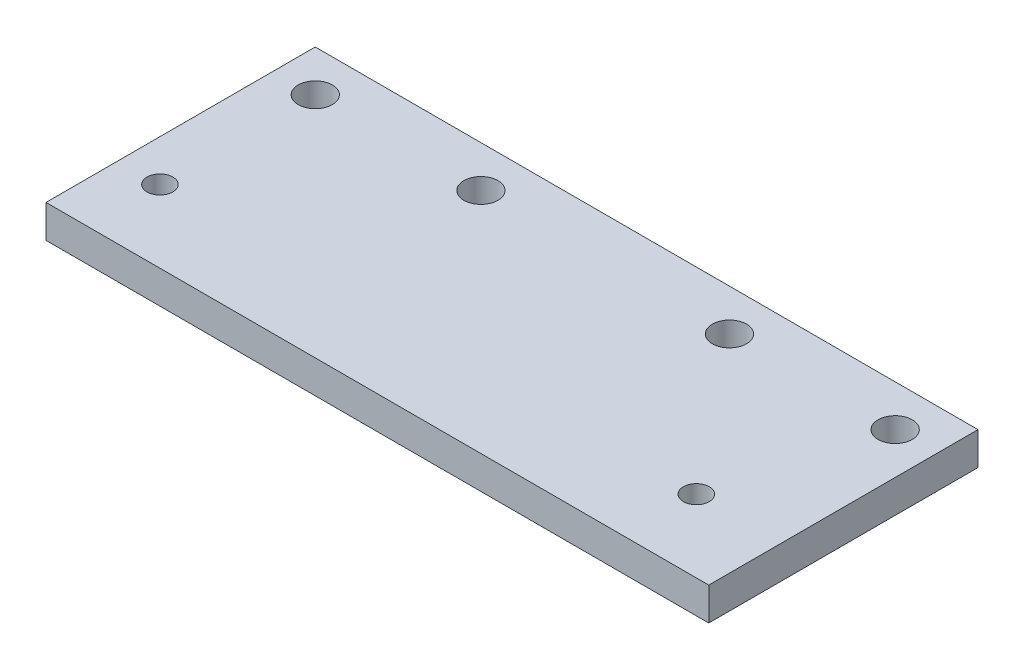
SolidWorks part; units mm, degrees
ref_plane "Front" through (0, 0, 0) normal (0, 0, 1) x (1, 0, 0)
ref_plane "Top" through (0, 0, 0) normal (0, 1, 0) x (1, 0, 0)
ref_plane "Right" through (0, 0, 0) normal (1, 0, 0) x (0, 0, -1)
sketch "Sketch1" plane through (0, 0, 0) normal (0, 1, 0) x (1, 0, 0)
  line L0 (0, 14) -> (64, 14)
  line L1 (0, 0) -> (64, 0)
  line L2 (0, 0) -> (0, 26)
  line L3 (0, 26) -> (64, 26)
  line L4 (64, 0) -> (64, 26)
  line L5 (0, 22) -> (64, 22)
  line L6 (0, 14) -> (0, 0)
  line L7 (0, 7) -> (4, 7)
  line L8 (64, 7) -> (55.8, 7)
  circle A0 centre (4, 22) radius 1.65
  circle A1 centre (20, 22) radius 1.65
  circle A2 centre (60, 22) radius 1.65
  circle A3 centre (44, 22) radius 1.65
  circle A4 centre (4, 7) radius 1.25
  circle A5 centre (55.8, 7) radius 1.25
  dimension "D6" = 3.3
  dimension "D8" = 3.3
  dimension "D10" = 3.3
  dimension "D11" = 16
  dimension "D13" = 8.2
  dimension "D1" = 12
  dimension "D2" = 14
  dimension "D3" = 4
  dimension "D4" = 64
  dimension "D5" = 4
  dimension "D7" = 4
  dimension "D9" = 16
  dimension "D12" = 4
extrude "Boss-Extrude1" add sketch "Sketch1" along normal blind 3.175 contours L1 L4 L0 L2 | A3 L5 A2 L4 L3 L2 A0 A1 | A3 L5 A1 A0 L2 L0 L4 A2
